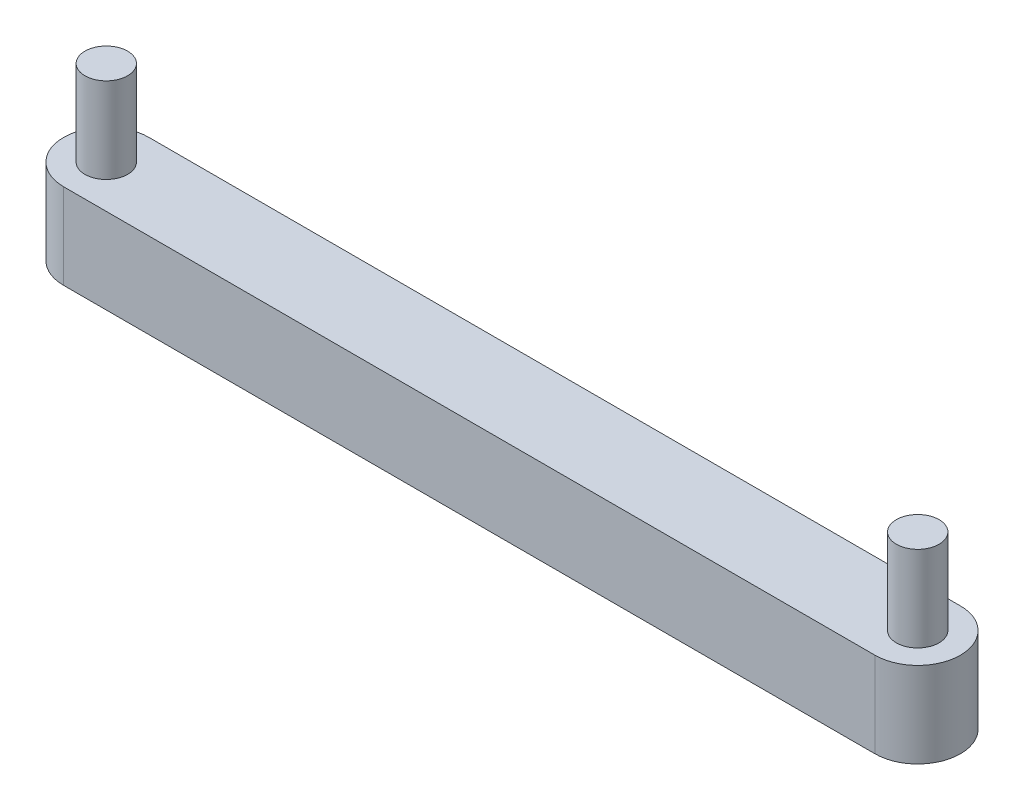
SolidWorks part; units mm, degrees
material "AISI 316 Annealed Stainless Steel Bar (SS)"
ref_plane "Front Plane" through (0, 0, 0) normal (0, 0, 1) x (1, 0, 0)
ref_plane "Top Plane" through (0, 0, 0) normal (0, 1, 0) x (1, 0, 0)
ref_plane "Right Plane" through (0, 0, 0) normal (1, 0, 0) x (0, 0, -1)
sketch "Sketch1" plane through (0, 0, 0) normal (0, 1, 0) x (1, 0, 0)
  line L0 (-47.5, 0) -> (47.5, 0) construction
  line L1 (-47.5, 5) -> (47.5, 5)
  line L2 (-47.5, -5) -> (47.5, -5)
  arc A0 (-47.5, 5) -> (-47.5, -5) centre (-47.5, 0) ccw
  arc A1 (47.5, -5) -> (47.5, 5) centre (47.5, 0) ccw
  point P2 (0, 0)
  dimension "D2" = 5
  dimension "D1" = 95
extrude "Boss-Extrude1" add sketch "Sketch1" along normal blind 10
sketch "Sketch2" plane through (0, 10, 0) normal (0, 1, 0) x (1, 0, 0)
  circle A0 centre (-47.5, 0) radius 2.5
  circle A1 centre (47.5, 0) radius 2.5
  dimension "D1" = 5
extrude "Boss-Extrude2" add sketch "Sketch2" along normal blind 10
